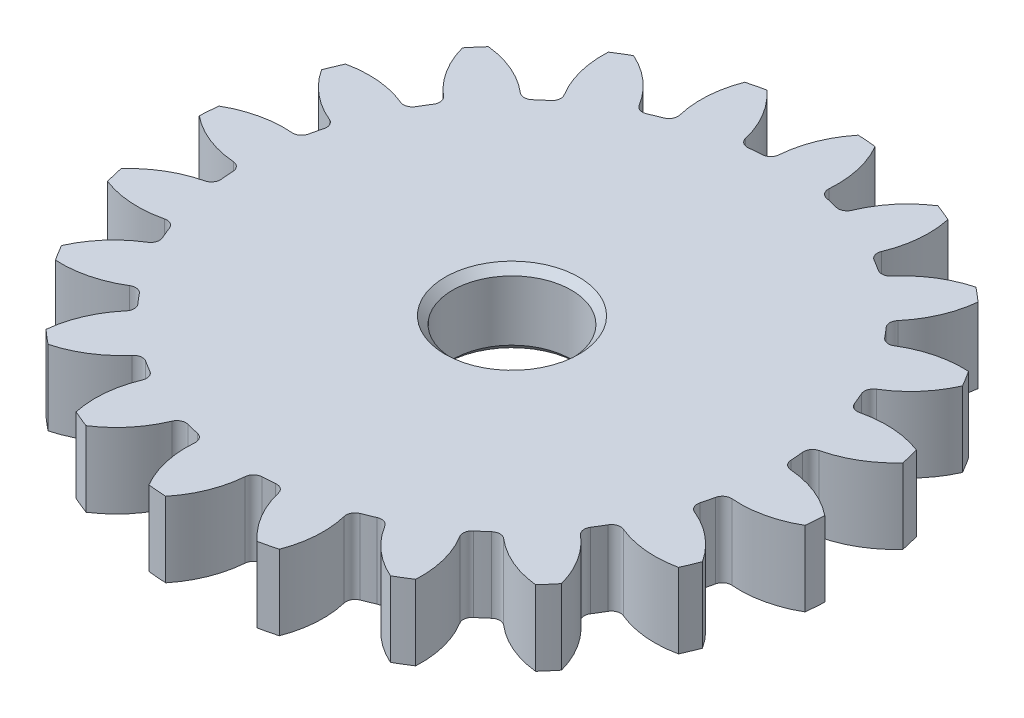
SolidWorks part; units mm, degrees
ref_plane "Alzado" through (0, 0, 0) normal (0, 0, 1) x (1, 0, 0)
ref_plane "Planta" through (0, 0, 0) normal (0, 1, 0) x (1, 0, 0)
ref_plane "Vista lateral" through (0, 0, 0) normal (1, 0, 0) x (0, 0, -1)
sketch "Croquis1" plane through (0, 0, 0) normal (0, 1, 0) x (1, 0, 0)
  line L0 (0, 0) -> (0, 35.9283) construction
  line L1 (0, 40) -> (12.856, 35.3207) construction
  line L2 (0, 0) -> (2.8687, 36.4125) construction
  line L3 (6.2638, 39.5065) -> (-7.1663, 36.8981) construction
  circle A0 centre (0, 0) radius 44 construction
  circle A1 centre (0, 0) radius 40 construction
  circle A2 centre (0, 0) radius 35.332 construction
  circle A3 centre (0, 0) radius 37.5876 construction
  arc A4 (2.2341, 43.9432) -> (-0.8251, 35.3224) centre (12.856, 35.3207) ccw
  arc A5 (4.6747, 43.751) -> (6.3462, 34.7574) centre (-7.1663, 36.8981) cw
  dimension "De" = 88
  dimension "Dp" = 80
  dimension "Di" = 70.664
  dimension "CT" = 75.1752
  dimension "e" = 6.2832
sketch "Croquis2" plane through (0, 0, 0) normal (0, 1, 0) x (1, 0, 0)
  circle A0 centre (0, 0) radius 35.332 construction
  circle A1 centre (0, 0) radius 44 construction
  arc A2 (6.3462, 34.7574) -> (4.6747, 43.751) centre (-7.1663, 36.8981) ccw construction
  arc A3 (2.2341, 43.9432) -> (-0.8251, 35.3224) centre (12.856, 35.3207) ccw construction
  arc A4 (-0.8251, 35.3224) -> (6.3462, 34.7574) centre (0, 0) ccw
  arc A5 (4.6747, 43.751) -> (2.2341, 43.9432) centre (0, 0) ccw
  arc A6 (6.3462, 34.7574) -> (4.6747, 43.751) centre (-7.1663, 36.8981) ccw
  arc A7 (2.2341, 43.9432) -> (-0.8251, 35.3224) centre (12.856, 35.3207) ccw
extrude "Saliente-Extruir1" add sketch "Croquis2" against normal blind 10
fillet "Redondeo1" radius 1.2 2 edges at (-0.8251, -5, -35.3224) (6.3462, -5, -34.7574)
pattern_circular "MatrizC1" count 20 over 360 about axis through (0, 0, 0) along (0, 1, 0) of "Saliente-Extruir1", "Redondeo1"
sketch "Croquis3" plane through (0, 0, 0) normal (0, 1, 0) x (1, 0, 0)
  circle A0 centre (0, 0) radius 7.92
  dimension "D1" = 15.84
extrude "Cortar-Extruir1" cut sketch "Croquis3" against normal blind 10
chamfer "Chaflán1" distance 1 angle 45 2 edges at (0, -10, 7.92) (0, 0, 7.92)
equation "\"M\"= 4'Modulo "
equation "\"N\"= 20'No. de Dientes"
equation "\"a\"= 20'Angulo de presion"
equation "\"De@Croquis1\"= \"M\" * ( \"N\" + 2 )'Diametro Externo"
equation "\"Dp@Croquis1\"= \"M\" * \"N\"'Diametro Primitivo"
equation "\"Di@Croquis1\"= \"Dp@Croquis1\" - ( 2 * \"M\" * 1.167 )'Diametro Interno"
equation "\"CT@Croquis1\"= \"Dp@Croquis1\" * 0.93969"
equation "\"e@Croquis1\"= \"M\" * 1.5708"
equation "\"r@Redondeo1\"= \"M\" * 0.3"
equation "\"D1@MatrizC1\"=\"N\""
